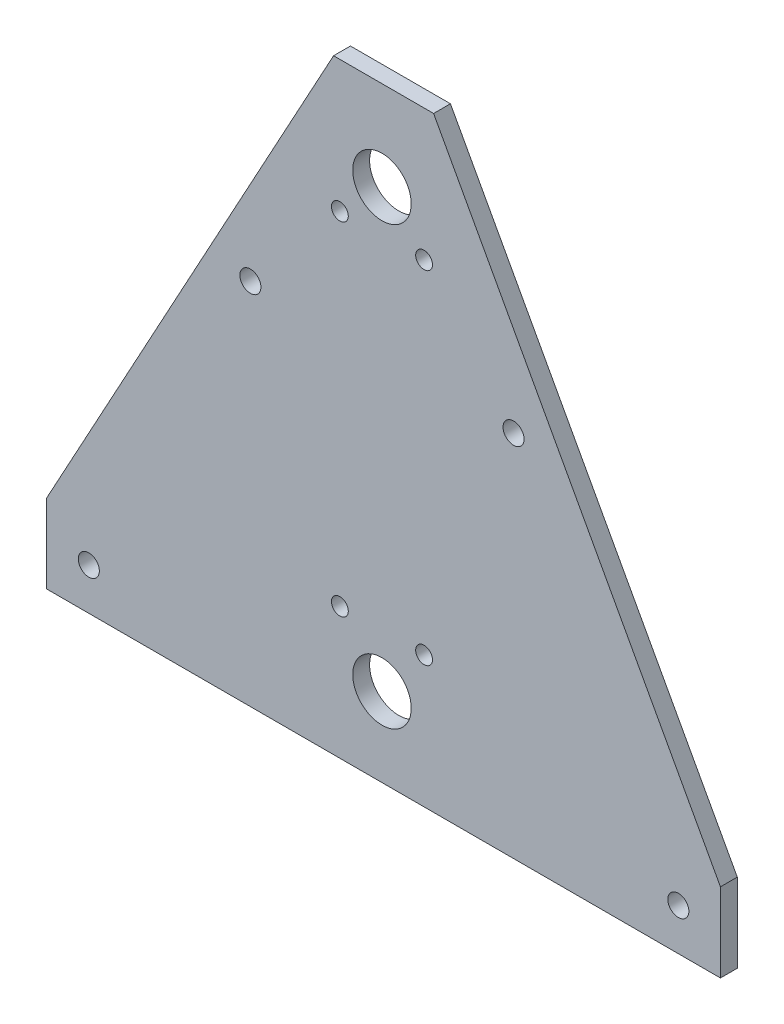
SolidWorks part; units mm, degrees
ref_plane "Front Plane" through (0, 0, 0) normal (0, 0, 1) x (1, 0, 0)
ref_plane "Top Plane" through (0, 0, 0) normal (0, 1, 0) x (1, 0, 0)
ref_plane "Right Plane" through (0, 0, 0) normal (1, 0, 0) x (0, 0, -1)
sketch "Sketch2" plane through (0, 0, 0) normal (0, 0, 1) x (1, 0, 0)
  line L0 (0, 0) -> (640, 0)
  line L1 (640, 0) -> (640, 75)
  line L2 (640, 75) -> (367.5104, 575)
  line L3 (367.5104, 575) -> (272.5104, 575)
  line L4 (272.5104, 575) -> (0, 75)
  line L5 (0, 75) -> (0, 0)
  line L6 (318.4763, -76.1802) -> (318.4763, 693.2816) construction
  line L7 (252.4939, 490) -> (372.5269, 490) construction
  line L8 (232.2981, 450) -> (394.8747, 450) construction
  line L9 (278.4763, 508.837) -> (278.4763, 428.4892) construction
  line L10 (358.4763, 508.837) -> (358.4763, 428.4892) construction
  line L11 (163.1746, 350) -> (461.7843, 350) construction
  line L12 (193.4763, 396.2326) -> (193.4763, 252.7294) construction
  line L13 (443.4763, 396.2326) -> (443.4763, 252.7294) construction
  line L14 (94.6982, 125) -> (541.3725, 125) construction
  line L15 (278.4763, 190.2148) -> (278.4763, 59.8341) construction
  line L16 (358.4763, 190.2148) -> (358.4763, 59.8341) construction
  line L17 (174.6091, 75) -> (453.5737, 75) construction
  line L18 (15.5721, 40) -> (612.7868, 40) construction
  line L19 (40, 75) -> (40, 4.5298) construction
  line L20 (600, 75) -> (600, 4.5298) construction
  circle A1 centre (318.4763, 490) radius 27.775
  circle A2 centre (278.4763, 450) radius 8
  circle A3 centre (358.4763, 450) radius 8
  circle A4 centre (193.4763, 350) radius 10
  circle A5 centre (443.4763, 350) radius 10
  circle A6 centre (278.4763, 125.0244) radius 8
  circle A7 centre (358.4763, 125.0244) radius 8
  circle A8 centre (318.4763, 75) radius 27.775
  circle A9 centre (40, 39.7649) radius 10
  circle A10 centre (600, 39.7649) radius 10
  dimension "D8" = 40
  dimension "D11" = 55.55
  dimension "D12" = 16
  dimension "D13" = 16
  dimension "D17" = 20
  dimension "D1" = 640
  dimension "D2" = 75
  dimension "D3" = 75
  dimension "D4" = 95
  dimension "D5" = 500
  dimension "D6" = 569.44
  dimension "D7" = 415
  dimension "D9" = 40
  dimension "D14" = 100
  dimension "D15" = 125
  dimension "D19" = 125
  dimension "D23" = 40
  dimension "D24" = 40
extrude "Boss-Extrude1" add sketch "Sketch2" along normal blind 16
